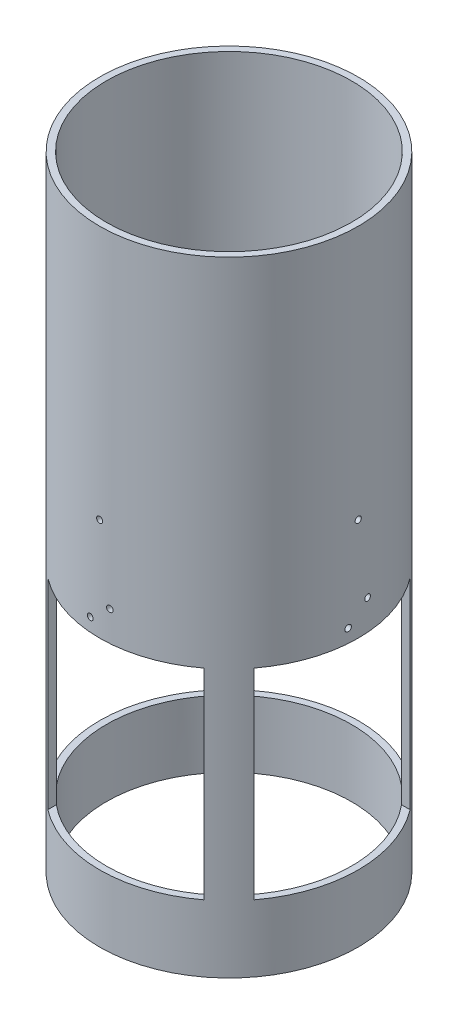
SolidWorks part; units mm, degrees
ref_plane "Front Plane" through (0, 0, 0) normal (0, 0, 1) x (1, 0, 0)
ref_plane "Top Plane" through (0, 0, 0) normal (0, 1, 0) x (1, 0, 0)
ref_plane "Right Plane" through (0, 0, 0) normal (1, 0, 0) x (0, 0, -1)
sketch "Sketch1" plane through (0, 0, 0) normal (0, 1, 0) x (1, 0, 0)
  circle A0 centre (0, 0) radius 73.66
  circle A1 centre (0, 0) radius 69.85
extrude "Boss-Extrude1" add sketch "Sketch1" along normal blind 355.6
sketch "Sketch3" plane through (0, 0, 0) normal (0, 1, 0) x (1, 0, 0)
  line L0 (-80.7173, 0) -> (81.0133, 0)
ref_plane "Plane2" through (73.66, 0, 0) normal (1, 0, 0) x (0, 0, -1)
sketch "Sketch4" plane through (73.66, 0, 0) normal (1, 0, 0) x (0, 0, -1)
  line L0 (0, 0) -> (0, 38.1) construction
  line L1 (44.45, 38.1) -> (-44.45, 38.1) construction
  line L2 (-44.45, 38.1) -> (44.45, 38.1)
  line L3 (-44.45, 38.1) -> (-44.45, 152.4)
  line L4 (44.45, 38.1) -> (44.45, 152.4)
  line L5 (-44.45, 152.4) -> (44.45, 152.4)
  point P5 (0, 38.1)
extrude "Cut-Extrude1" cut sketch "Sketch4" against normal blind 76.2
pattern_circular "CirPattern1" count 4 over 360 about axis through (0, 0, 0) along (0, 1, 0) of "Cut-Extrude1"
sketch "Sketch5" plane through (73.66, 0, 0) normal (1, 0, 0) x (0, 0, -1)
  line L0 (0, 152.4) -> (0, 160.02) construction
  line L1 (-44.45, 152.4) -> (44.45, 152.4) construction
  line L2 (0, 160.02) -> (-5.5562, 160.02) construction
  line L3 (0, 152.4) -> (0, 169.545) construction
  line L4 (0, 169.545) -> (5.5562, 169.545) construction
  line L5 (0, 152.4) -> (0, 210.82) construction
  circle A0 centre (0, 210.82) radius 1.7526
  circle A1 centre (5.5562, 169.545) radius 1.7526
  circle A2 centre (-5.5562, 160.02) radius 1.7526
extrude "Cut-Extrude2" cut sketch "Sketch5" against normal blind 76.2
pattern_circular "CirPattern2" count 4 over 360 about axis through (0, 355.6, 0) along (0, -1, 0) of "Cut-Extrude2"
